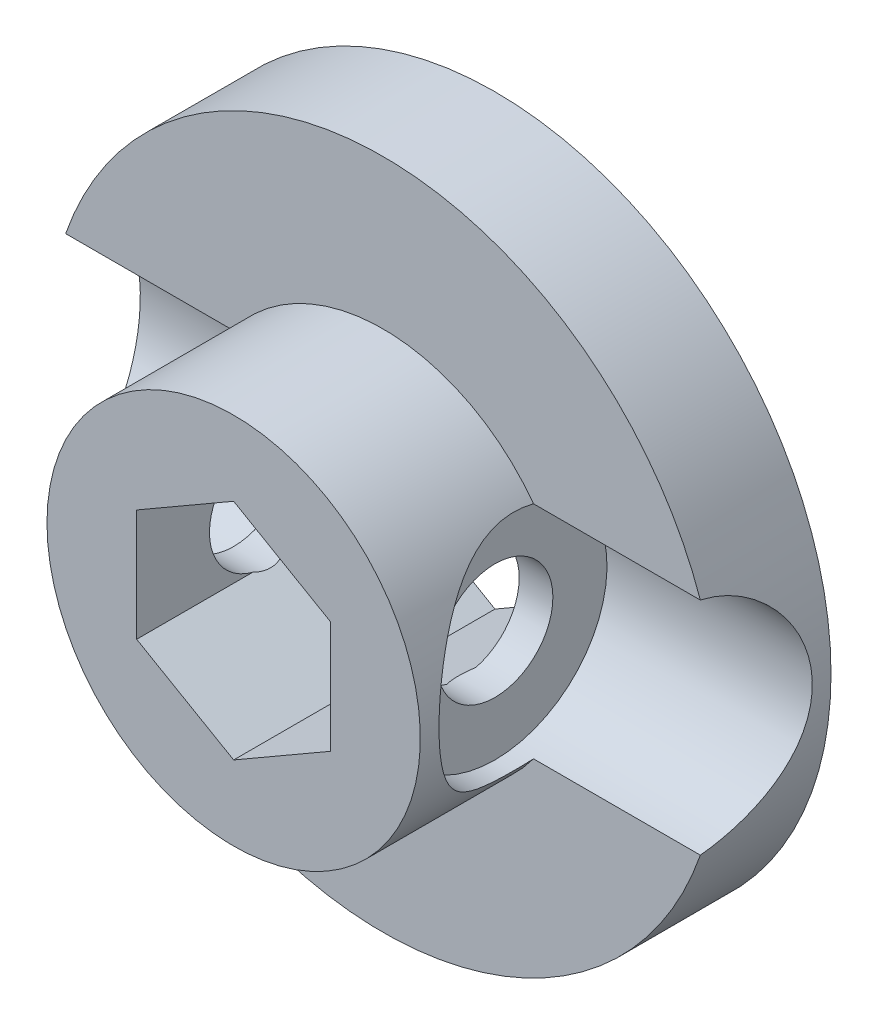
SolidWorks part; units mm, degrees
ref_plane "Front Plane" through (0, 0, 0) normal (0, 0, 1) x (1, 0, 0)
ref_plane "Top Plane" through (0, 0, 0) normal (0, 1, 0) x (1, 0, 0)
ref_plane "Right Plane" through (0, 0, 0) normal (1, 0, 0) x (0, 0, -1)
sketch "Sketch1" plane through (0, 0, 0) normal (0, 0, 1) x (1, 0, 0)
  circle A0 centre (0, 0) radius 9
  circle A1 centre (0, 0) radius 5
extrude "Boss-Extrude4" add sketch "Sketch1" along normal blind 3
sketch "Sketch3" plane through (0, 0, 0) normal (0, 0, -1) x (-1, 0, 0)
  line L0 (0, -3) -> (0, 3) construction
  line L1 (-2.5981, -1.5) -> (2.5981, 1.5) construction
  line L2 (2.5981, -1.5) -> (-2.5981, 1.5) construction
  line L3 (0, 3) -> (-2.5981, 1.5)
  line L4 (-2.5981, 1.5) -> (-2.5981, -1.5)
  line L5 (-2.5981, -1.5) -> (0, -3)
  line L6 (0, -3) -> (2.5981, -1.5)
  line L7 (2.5981, -1.5) -> (2.5981, 1.5)
  line L8 (2.5981, 1.5) -> (0, 3)
  circle A0 centre (0, 0) radius 5
  circle A1 centre (0, 0) radius 3 construction
  point P7 (0, 0)
  point P10 (0, 0)
  point P13 (0, 0)
extrude "Boss-Extrude5" add sketch "Sketch3" against normal blind 7
ref_plane "Plane1" through (0, 0, 0) normal (-1, 0, 0) x (0, 0, 1)
sketch "Sketch5" plane through (0, 0, 0) normal (-1, 0, 0) x (0, 0, 1)
  line L0 (7, 5) -> (7, -5) construction
  line L1 (7, 0) -> (3.5, 0) construction
  circle A0 centre (3.5, 0) radius 1.55
extrude "Cut-Extrude1" cut sketch "Sketch5" against normal blind 5 and the other way blind 5
ref_plane "Plane2" through (-3.5, 0, 0) normal (-1, 0, 0) x (0, 0, 1)
ref_plane "Plane3" through (3.5, 0, 0) normal (-1, 0, 0) x (0, 0, 1)
sketch "Sketch6" plane through (-3.5, 0, 0) normal (-1, 0, 0) x (0, 0, 1)
  circle A0 centre (3.5, 0) radius 3
extrude "Cut-Extrude2" cut sketch "Sketch6" along normal blind 5.5
sketch "Sketch7" plane through (3.5, 0, 0) normal (-1, 0, 0) x (0, 0, 1)
  circle A0 centre (3.5, 0) radius 3
extrude "Cut-Extrude3" cut sketch "Sketch7" against normal blind 5.5 contours A0
